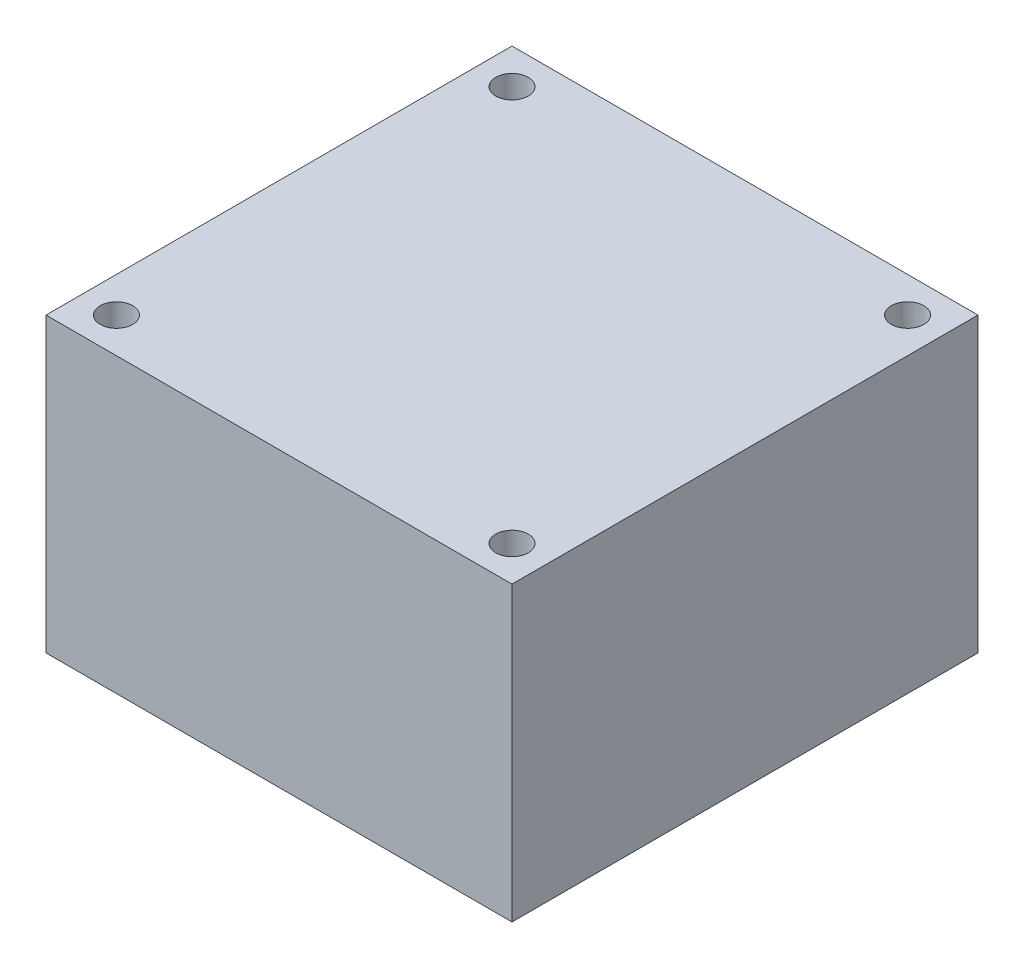
SolidWorks part; units mm, degrees
ref_plane "前视基准面" through (0, 0, 0) normal (0, 0, 1) x (1, 0, 0)
ref_plane "上视基准面" through (0, 0, 0) normal (0, 1, 0) x (1, 0, 0)
ref_plane "右视基准面" through (0, 0, 0) normal (1, 0, 0) x (0, 0, -1)
sketch "草图1" plane through (0, 0, 0) normal (0, 1, 0) x (1, 0, 0)
  line L1 (-21.5, 21.5) -> (21.5, 21.5)
  line L2 (-21.5, 21.5) -> (-21.5, -21.5)
  line L3 (-21.5, -21.5) -> (21.5, -21.5)
  line L4 (21.5, 21.5) -> (21.5, -21.5)
  line L5 (-21.5, 21.5) -> (21.5, -21.5) construction
  line L6 (-21.5, -21.5) -> (21.5, 21.5) construction
  line L7 (-18.25, 18.25) -> (18.25, 18.25) construction
  line L8 (-18.25, 18.25) -> (-18.25, -18.25) construction
  line L9 (-18.25, -18.25) -> (18.25, -18.25) construction
  line L10 (18.25, 18.25) -> (18.25, -18.25) construction
  line L11 (-18.25, 18.25) -> (18.25, -18.25) construction
  line L12 (-18.25, -18.25) -> (18.25, 18.25) construction
  circle A0 centre (-18.25, 18.25) radius 1.5
  circle A1 centre (18.25, 18.25) radius 1.5
  circle A2 centre (-18.25, -18.25) radius 1.5
  circle A3 centre (18.25, -18.25) radius 1.5
  point P0 (0, 0)
  point P6 (0, 0)
  dimension "D5" = 3
  dimension "D1" = 43
  dimension "D2" = 43
  dimension "D3" = 36.5
  dimension "D4" = 36.5
extrude "凸台-拉伸1" add sketch "草图1" along normal blind 27
